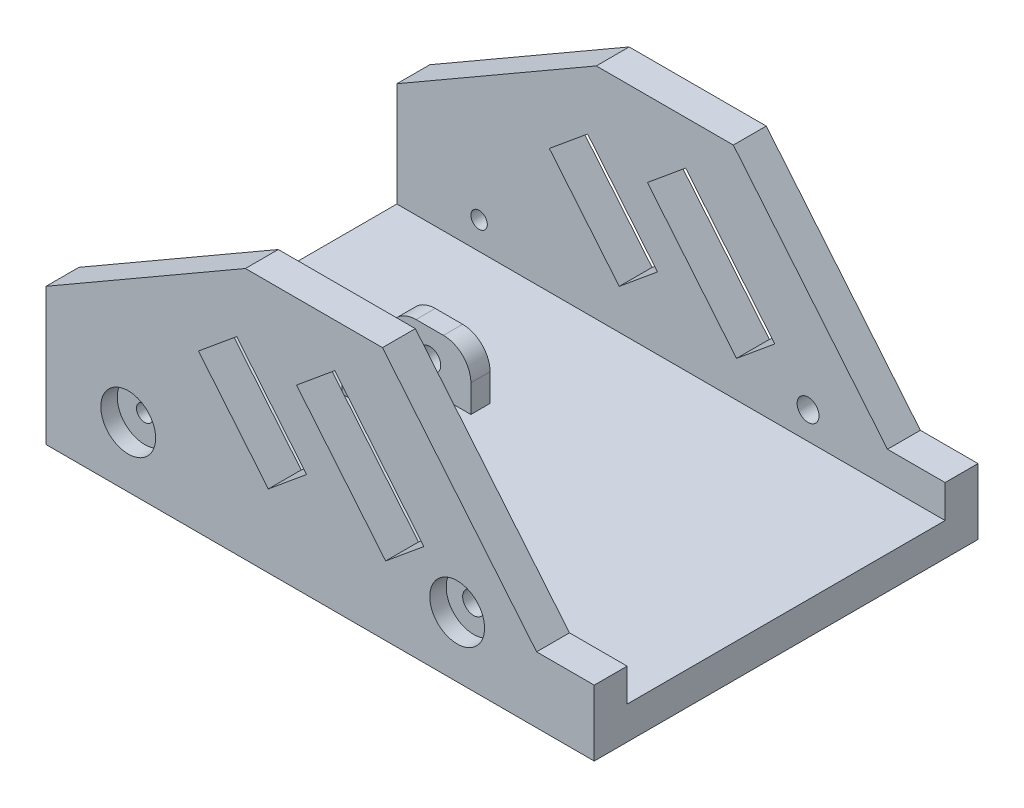
SolidWorks part; units mm, degrees
material "ABS"
ref_plane "Front Plane" through (0, 0, 0) normal (0, 0, 1) x (1, 0, 0)
ref_plane "Top Plane" through (0, 0, 0) normal (0, 1, 0) x (1, 0, 0)
ref_plane "Right Plane" through (0, 0, 0) normal (1, 0, 0) x (0, 0, -1)
sketch "Sketch1" plane through (0, 0, 0) normal (0, 1, 0) x (1, 0, 0)
  line L0 (-50, 35) -> (-50, -35)
  line L1 (-50, -35) -> (50, -35)
  line L3 (-50, 35) -> (50, 35)
  line L5 (50, 35) -> (50, -35)
  point P0 (0, 0)
  dimension "D1" = 50
  dimension "D3" = 50
extrude "Boss-Extrude1" add sketch "Sketch1" along normal blind 6
sketch "Sketch2" plane through (0, 6, 0) normal (0, 1, 0) x (1, 0, 0)
  line L1 (-50, 35) -> (50, 35)
  line L3 (-50, 29) -> (50, 29)
  line L6 (50, -35) -> (-50, -35)
  line L8 (50, -29) -> (-50, -29)
  line L10 (-50, -29) -> (-50, -35)
  line L11 (-50, 35) -> (-50, -35) construction
  line L12 (-50, 35) -> (-50, 29)
  line L13 (50, 35) -> (50, 29)
  line L14 (50, -35) -> (50, 35) construction
  line L15 (50, -35) -> (50, -29)
extrude "Boss-Extrude2" add sketch "Sketch2" along normal blind 50
sketch "Sketch3" plane through (0, 0, 35) normal (0, 0, 1) x (1, 0, 0)
  line L0 (-50, 0) -> (50, 0) construction
  line L3 (-50, 56) -> (-50, 0) construction
  line L4 (50, 56) -> (50, 0) construction
  circle A0 centre (-35, 11) radius 1.5
  circle A1 centre (25, 11) radius 2
  dimension "D1" = 4
  dimension "D2" = 3
  dimension "D3" = 11
  dimension "D4" = 15
  dimension "D5" = 25
extrude "Cut-Extrude1" cut sketch "Sketch3" against normal through all both and the other way through all
sketch "Sketch4" plane through (0, 0, 35) normal (0, 0, 1) x (1, 0, 0)
  line L0 (-50, 25) -> (3.6936, 56)
  line L1 (-50, 56) -> (-50, 0) construction
  line L2 (-50, 56) -> (50, 56) construction
  line L3 (-50, 25) -> (-50, 56)
  line L4 (-50, 56) -> (3.6936, 56)
  dimension "D1" = 120
  dimension "D2" = 25
extrude "Cut-Extrude2" cut sketch "Sketch4" against normal through all both and the other way through all
sketch "Sketch5" plane through (0, 0, 35) normal (0, 0, 1) x (1, 0, 0)
  line L0 (26.8468, 56) -> (50, 28)
  line L1 (3.6936, 56) -> (50, 56) construction
  line L2 (50, 56) -> (50, 0) construction
  line L3 (50, 28) -> (50, 56)
  line L4 (50, 56) -> (26.8468, 56)
extrude "Cut-Extrude3" cut sketch "Sketch5" against normal through all
sketch "Sketch6" plane through (0, 0, 35) normal (0, 0, 1) x (1, 0, 0)
  line L0 (16.6004, 47.5272) -> (39.7536, 19.5272)
  line L1 (39.7536, 19.5272) -> (47.4601, 25.8998)
  line L2 (47.4601, 25.8998) -> (24.3069, 53.8998)
  line L3 (24.3069, 53.8998) -> (16.6004, 47.5272)
  line L4 (26.8468, 56) -> (50, 28) construction
  dimension "D1" = 10
extrude "Cut-Extrude4" cut sketch "Sketch6" against normal through all both and the other way through all
sketch "Sketch7" plane through (0, 0, 35) normal (0, 0, 1) x (1, 0, 0)
  line L0 (2.6732, 38.0131) -> (-4.3047, 32.243)
  line L1 (-4.3047, 32.243) -> (11.9486, 12.5874)
  line L2 (11.9486, 12.5874) -> (18.9265, 18.3574)
  line L3 (18.9265, 18.3574) -> (2.6732, 38.0131)
  line L4 (-15.2123, 34.4494) -> (-22.1903, 28.6793)
  line L5 (-22.1903, 28.6793) -> (-9.4452, 13.2663)
  line L6 (-9.4452, 13.2663) -> (-2.4673, 19.0363)
  line L7 (-2.4673, 19.0363) -> (-15.2123, 34.4494)
  dimension "D1" = 7
  dimension "D2" = 20
extrude "Cut-Extrude5" cut sketch "Sketch7" against normal through all both and the other way through all
sketch "Sketch9" plane through (0, 6, 0) normal (0, 1, 0) x (1, 0, 0)
  line L0 (0, 0) -> (-50000, 0) construction
  line L1 (-25, 6) -> (-10, 6)
  line L2 (-25, 6) -> (-25, 2.5)
  line L3 (-25, 2.5) -> (-10, 2.5)
  line L4 (-10, 6) -> (-10, 2.5)
  line L5 (-10, -2.5) -> (-25, -2.5)
  line L6 (-10, -2.5) -> (-10, -6)
  line L7 (-10, -6) -> (-25, -6)
  line L8 (-25, -2.5) -> (-25, -6)
  line L9 (-50, 29) -> (-50, -29) construction
  dimension "D1" = 2.5
  dimension "D2" = 2.5
  dimension "D3" = 3.5
  dimension "D4" = 3.5
  dimension "D5" = 15
  dimension "D6" = 25
extrude "Boss-Extrude3" add sketch "Sketch9" along normal blind 10
sketch "Sketch11" plane through (0, 0, -2.5) normal (0, 0, 1) x (1, 0, 0)
  line L0 (-25, 16) -> (-25, 6) construction
  line L2 (-25, 16) -> (-10, 16) construction
  circle A0 centre (-17.5, 11) radius 2
  dimension "D1" = 4
  dimension "D2" = 7.5
  dimension "D3" = 5
extrude "Cut-Extrude8" cut sketch "Sketch11" against normal up to surface and the other way up to surface
fillet "Fillet1" radius 5 1 edges at (-25, 16, -4.25)
fillet "Fillet2" radius 5 1 edges at (-10, 16, -4.25)
fillet "Fillet3" radius 5 1 edges at (-25, 16, 4.25)
fillet "Fillet4" radius 5 1 edges at (-10, 16, 4.25)
sketch "Sketch13" plane through (0, 0, -35) normal (0, 0, -1) x (-1, 0, 0)
  line L0 (-50, 12) -> (-39.4877, 12)
  line L1 (-50, 28) -> (-50, 0) construction
  line L2 (-39.4877, 12) -> (-11.3731, 46)
  line L3 (-11.3731, 46) -> (13.6269, 46)
  line L4 (50, 25) -> (-3.6936, 56) construction
  line L5 (-16.6004, 47.5272) -> (-39.7536, 19.5272) construction
  line L6 (-50, 0) -> (50, 0) construction
  line L7 (-26.8468, 56) -> (-3.6936, 56) construction
  line L8 (-50, 12) -> (-50, 28)
  line L9 (-50, 28) -> (-26.8468, 56)
  line L10 (-26.8468, 56) -> (-3.6936, 56)
  line L11 (-3.6936, 56) -> (13.6269, 46)
  dimension "D1" = 12
  dimension "D2" = 25
  dimension "D3" = 10
extrude "Cut-Extrude9" cut sketch "Sketch13" against normal through all
sketch "Sketch14" plane through (0, 0, 35) normal (0, 0, 1) x (1, 0, 0)
  circle A0 centre (25, 11) radius 5
  dimension "D1" = 10
extrude "Cut-Extrude10" cut sketch "Sketch14" against normal blind 3
sketch "Sketch15" plane through (0, 0, -35) normal (0, 0, -1) x (-1, 0, 0)
  circle A0 centre (-25, 11) radius 5
  dimension "D1" = 10
extrude "Cut-Extrude11" cut sketch "Sketch15" against normal blind 3
sketch "Sketch16" plane through (0, 0, -35) normal (0, 0, -1) x (-1, 0, 0)
  circle A0 centre (35, 11) radius 5
  dimension "D1" = 10
extrude "Cut-Extrude12" cut sketch "Sketch16" against normal blind 3
sketch "Sketch17" plane through (0, 0, 35) normal (0, 0, 1) x (1, 0, 0)
  circle A0 centre (-35, 11) radius 5
  dimension "D1" = 10
extrude "Cut-Extrude13" cut sketch "Sketch17" against normal blind 3
